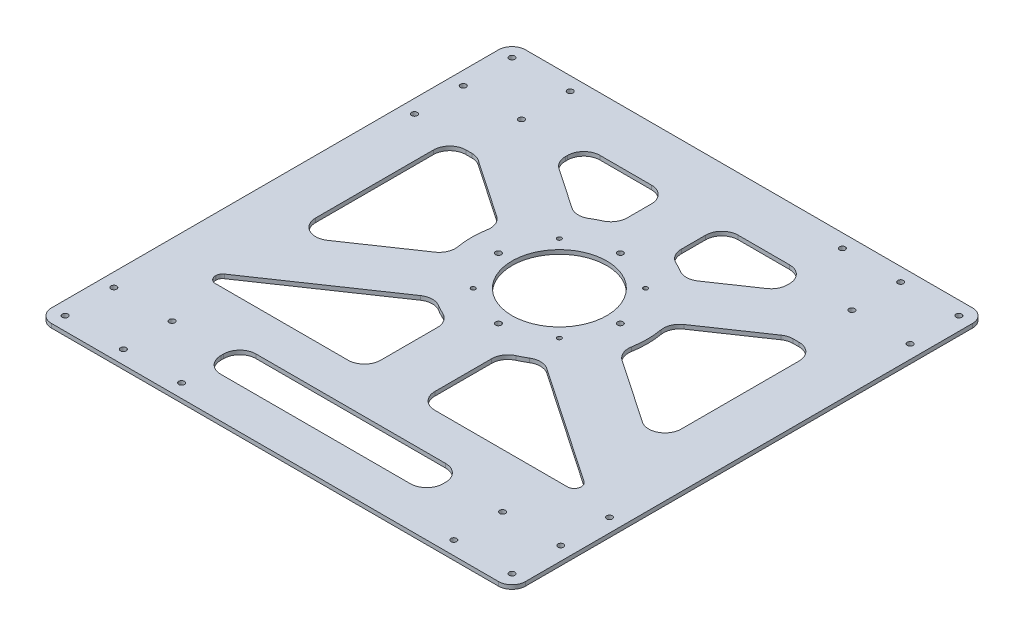
SolidWorks part; units mm, degrees
ref_plane "Front Plane" through (0, 0, 0) normal (0, 0, 1) x (1, 0, 0)
ref_plane "Top Plane" through (0, 0, 0) normal (0, 1, 0) x (1, 0, 0)
ref_plane "Right Plane" through (0, 0, 0) normal (1, 0, 0) x (0, 0, -1)
sketch "Sketch1" plane through (0, 0, 0) normal (0, 1, 0) x (1, 0, 0)
  line L1 (0, 0) -> (350, 0)
  line L2 (0, 0) -> (0, 350)
  line L3 (0, 350) -> (350, 350)
  line L4 (350, 0) -> (350, 350)
  dimension "D1" = 350
  dimension "D2" = 350
extrude "Boss-Extrude1" add sketch "Sketch1" along normal blind 3
fillet "Fillet1" radius 10 4 edges at (0, 1.5, -350) (350, 1.5, -350) (350, 1.5, 0) (0, 1.5, 0)
sketch "Sketch2" plane through (0, 3, 0) normal (0, 1, 0) x (1, 0, 0)
  line L0 (10, 340) -> (53, 340) construction
  line L1 (53, 340) -> (53, 304) construction
  line L2 (53, 304) -> (10, 304) construction
  line L3 (10, 304) -> (10, 340) construction
  line L4 (340, 350) -> (10, 350) construction
  line L5 (0, 340) -> (0, 10) construction
  line L6 (0, 175) -> (350, 175) construction
  line L7 (350, 10) -> (350, 340) construction
  line L8 (175, 350) -> (175, 0) construction
  line L9 (10, 0) -> (340, 0) construction
  circle A0 centre (10, 340) radius 2.1
  circle A1 centre (53, 340) radius 2.1
  circle A2 centre (53, 304) radius 2.1
  circle A3 centre (10, 304) radius 2.1
  circle A128 centre (10, 286) radius 2.1 [skipped]
  circle A129 centre (53, 286) radius 2.1 [skipped]
  circle A136 centre (254, 340) radius 2.1
  circle A137 centre (340, 82) radius 2.1
  circle A138 centre (297, 304) radius 2.1
  circle A139 centre (340, 304) radius 2.1
  circle A140 centre (297, 340) radius 2.1
  circle A141 centre (340, 340) radius 2.1
  circle A142 centre (340, 10) radius 2.1
  circle A143 centre (340, 46) radius 2.1
  circle A144 centre (297, 10) radius 2.1
  circle A145 centre (297, 46) radius 2.1
  circle A146 centre (53, 10) radius 2.1
  circle A147 centre (53, 46) radius 2.1
  circle A148 centre (10, 46) radius 2.1
  circle A149 centre (10, 10) radius 2.1
  circle A150 centre (53, 322) radius 2.1 [skipped]
  circle A151 centre (10, 322) radius 2.1 [skipped]
  circle A152 centre (96, 10) radius 2.1
  circle A153 centre (10, 268) radius 2.1
  point P52 (0, 0)
  point P53 (0, 0)
  point P54 (0, 0)
  point P55 (0, 0)
  point P56 (0, 0)
  point P57 (0, 0)
  point P58 (0, 0)
  dimension "D1" = 4.2
  dimension "D2" = 10
  dimension "D3" = 10
  dimension "D4" = 43
  dimension "D5" = 36
  dimension "D7" = 43
  dimension "D9" = 43
  dimension "D8" = 36
  dimension "D10" = 36
  dimension "D6" = 2
extrude "Cut-Extrude1" cut sketch "Sketch2" against normal through all
sketch "Sketch3" plane through (0, 3, 0) normal (0, 1, 0) x (1, 0, 0)
  line L0 (175, 350) -> (175, 0) construction
  line L9 (340, 350) -> (10, 350) construction
  line L10 (10, 0) -> (340, 0) construction
  line L11 (0, 175) -> (350, 175) construction
  line L12 (0, 340) -> (0, 10) construction
  line L13 (350, 10) -> (350, 340) construction
  line L14 (93, 290) -> (310, 142.3142)
  line L15 (40, 264) -> (310, 264)
  line L16 (40, 264) -> (40, 86)
  line L17 (40, 86) -> (310, 86)
  line L18 (310, 264) -> (310, 86)
  line L19 (93, 310) -> (257, 310)
  line L20 (93, 310) -> (93, 40)
  line L21 (93, 40) -> (257, 40)
  line L22 (257, 310) -> (257, 40)
  line L27 (60.109, 264) -> (310, 93.9293)
  line L28 (257, 290) -> (40, 142.3142)
  line L29 (289.891, 264) -> (40, 93.9293)
  line L30 (139.4531, 210) -> (210.5469, 210) construction
  line L32 (155, 310) -> (195, 310)
  line L33 (155, 310) -> (155, 40)
  line L34 (155, 40) -> (195, 40)
  line L35 (195, 310) -> (195, 40)
  line L36 (93, 40) -> (257, 40)
  line L37 (93, 40) -> (93, 30)
  line L38 (93, 30) -> (257, 30)
  line L39 (257, 40) -> (257, 30)
  circle A2 centre (175, 210) radius 35
  circle A3 centre (175, 210) radius 65
  circle A6 centre (297, 340) radius 2.1 construction
  circle A7 centre (297, 304) radius 2.1 construction
  point P4 (40, 175)
  point P5 (175, 264)
  point P22 (93, 175)
  point P27 (175, 310)
  point P31 (175, 310)
  dimension "D5" = 70
  dimension "D6" = 130
  dimension "D1" = 40
  dimension "D2" = 40
  dimension "D3" = 40
  dimension "D4" = 40
  dimension "D7" = 100
  dimension "D8" = 40
  dimension "D9" = 20
  dimension "D10" = 40
  dimension "D11" = 10
extrude "Cut-Extrude2" cut sketch "Sketch3" against normal blind 10 contours A3 L33 L19 L20 L14 L15 | A3 L15 L28 L22 L19 L35 | A3 L15 L14 | A3 L28 L15 | L28 L20 L27 L15 L16 | A3 L27 L20 L28 | A3 L14 L22 L29 | L15 L29 L22 L14 L18 | L27 L22 L17 L18 | A3 L35 L17 L22 L27 | L20 L29 L16 L17 | A3 L29 L20 L17 L33 | L35 A2 L28 L14 | L14 A2 L35 | L28 A2 L14 | L33 A2 L28 | L14 A2 L33 L28 | L35 L14 L28 L33 L27 L29 | L28 A2 L27 L33 | L27 A2 L33 | L33 A2 L29 L27 | L29 A2 L27 | L27 A2 L35 L29 | L35 A2 L29 | L29 A2 L14 L35 | L17 L35 L21 L22 | L33 L17 L20 L21 | L35 L17 L33 L21 | L39 L21 L37 L38
sketch "Sketch6" plane through (0, 3, 0) normal (0, 1, 0) x (1, 0, 0)
  line L0 (257, 86) -> (257, 30) construction
  line L1 (93, 86) -> (257, 86)
  line L2 (93, 86) -> (93, 56)
  line L3 (93, 56) -> (257, 56)
  line L4 (257, 86) -> (257, 56)
  line L5 (257, 86) -> (310, 86) construction
  dimension "D1" = 30
extrude "Boss-Extrude2" add sketch "Sketch6" against normal up to surface (3 mm away) up to face at (175, 0, -245)
fillet "Fillet2" radius 12 30 edges at (237.3815, 1.5, -191.7369) (237.3815, 1.5, -228.2631) (289.891, 1.5, -264) (310, 1.5, -264) (310, 1.5, -142.3142) (112.6185, 1.5, -191.7369) (40, 1.5, -142.3142) (40, 1.5, -264) (60.109, 1.5, -264) (112.6185, 1.5, -228.2631) (214.876, 1.5, -261.3313) (195, 1.5, -271.8466) (195, 1.5, -310) (257, 1.5, -310) (257, 1.5, -290) (214.876, 1.5, -158.6687) (257, 1.5, -30) (93, 1.5, -30) (135.124, 1.5, -158.6687) (155, 1.5, -148.1534) (155, 1.5, -86) (195, 1.5, -86) (195, 1.5, -148.1534) (155, 1.5, -271.8466) (135.124, 1.5, -261.3313) (93, 1.5, -290) (93, 1.5, -310) (155, 1.5, -310) (257, 1.5, -56) (93, 1.5, -56)
fillet "Fillet3" radius 5 4 edges at (310, 1.5, -86) (310, 1.5, -93.9293) (40, 1.5, -86) (40, 1.5, -93.9293)
sketch "Sketch5" plane through (0, 3, 0) normal (0, 1, 0) x (1, 0, 0)
  line L0 (175, 255) -> (175, 210) construction
  line L2 (206.8198, 241.8198) -> (175, 210) construction
  circle A0 centre (175, 210) radius 45 construction
  circle A1 centre (175, 255) radius 2.1
  circle A2 centre (220, 210) radius 2.1
  circle A3 centre (175, 165) radius 2.1
  circle A4 centre (130, 210) radius 2.1
  circle A9 centre (206.8198, 241.8198) radius 1.6
  circle A10 centre (206.8198, 178.1802) radius 1.6
  circle A11 centre (143.1802, 178.1802) radius 1.6
  circle A12 centre (143.1802, 241.8198) radius 1.6
  point P22 (175, 210)
  point P39 (175, 210)
  dimension "D1" = 90
  dimension "D2" = 4.2
  dimension "D4" = 4
  dimension "3.2" = 3.2
  dimension "D5" = 45
  dimension "D3" = 4
extrude "Cut-Extrude4" cut sketch "Sketch5" against normal blind 10
